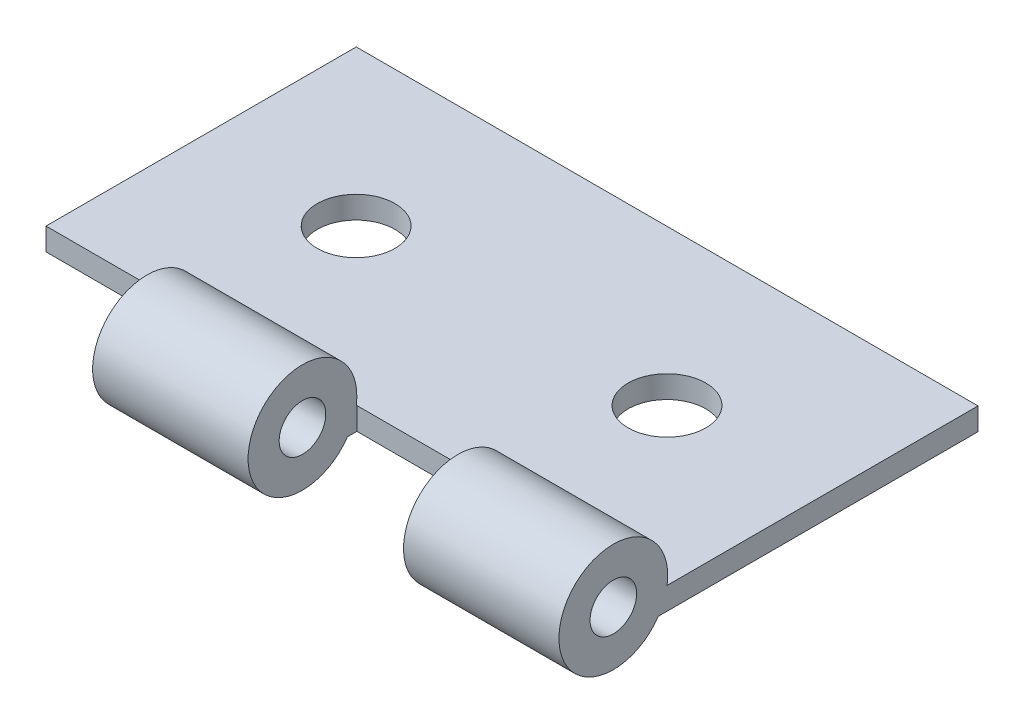
SolidWorks part; units mm, degrees
ref_plane "Front Plane" through (0, 0, 0) normal (0, 0, 1) x (1, 0, 0)
ref_plane "Top Plane" through (0, 0, 0) normal (0, 1, 0) x (1, 0, 0)
ref_plane "Right Plane" through (0, 0, 0) normal (1, 0, 0) x (0, 0, -1)
sketch "Sketch4" plane through (0, 0, 0) normal (1, 0, 0) x (0, 0, -1)
  line L0 (0, 0) -> (0, -2.4998) construction
  line L1 (3.6755, -2.4998) -> (29.7941, -2.4998)
  line L2 (29.7941, -2.4998) -> (29.7941, -0.671)
  line L3 (29.7941, -0.671) -> (4.3941, -0.671)
  circle A0 centre (0, 0) radius 4.445
  circle A1 centre (0, 0) radius 1.905
  dimension "D1" = 8.89
  dimension "D4" = 3.81
  dimension "D2" = 1.8288
  dimension "D3" = 25.4
extrude "Boss-Extrude2" add sketch "Sketch4" along normal blind 50.8
ref_plane "Plane1" through (0, 14.569, 0) normal (0, 1, 0) x (1, 0, 0)
sketch "Sketch5" plane through (0, 14.569, 0) normal (0, 1, 0) x (1, 0, 0)
  line L0 (0, -4.445) -> (50.8, -4.445) construction
  line L1 (0, 4.445) -> (12.7, 4.445)
  line L2 (0, 4.445) -> (0, -4.445)
  line L3 (0, -4.445) -> (12.7, -4.445)
  line L4 (12.7, 4.445) -> (12.7, -4.445)
  line L5 (12.7, 4.445) -> (25.4, 4.445) construction
  line L6 (50.8, 4.445) -> (0, 4.445) construction
  line L8 (25.4, 4.445) -> (38.1, 4.445)
  line L9 (25.4, 4.445) -> (25.4, -4.445)
  line L10 (25.4, -4.445) -> (38.1, -4.445)
  line L11 (38.1, 4.445) -> (38.1, -4.445)
  dimension "D1" = 12.7
extrude "Cut-Extrude2" cut sketch "Sketch5" against normal through all
sketch "Sketch6" plane through (0, -0.671, 0) normal (0, 1, 0) x (1, 0, 0)
  line L0 (25.3633, 17.1195) -> (12.6633, 17.1195) construction
  line L1 (25.3633, 17.1195) -> (25.3633, 21.2392) construction
  circle A0 centre (12.6633, 17.1195) radius 3.175
  circle A1 centre (38.0633, 17.1195) radius 3.175
  dimension "D2" = 6.35
  dimension "D1" = 12.7
extrude "Cut-Extrude3" cut sketch "Sketch6" against normal through all
